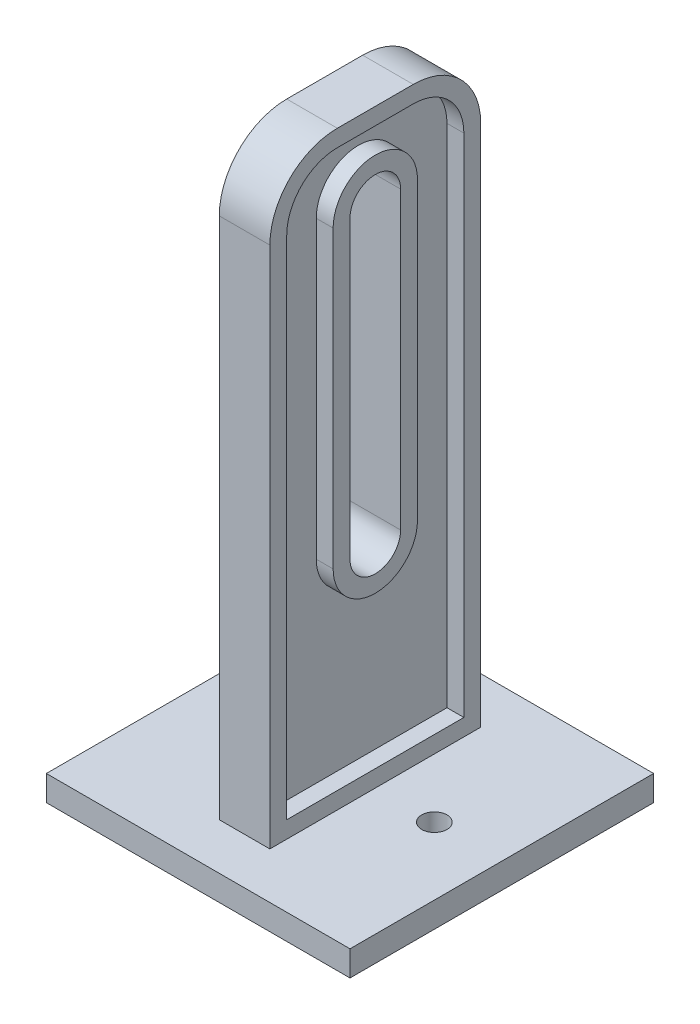
SolidWorks part; units mm, degrees
ref_plane "Front Plane" through (0, 0, 0) normal (0, 0, 1) x (1, 0, 0)
ref_plane "Top Plane" through (0, 0, 0) normal (0, 1, 0) x (1, 0, 0)
ref_plane "Right Plane" through (0, 0, 0) normal (1, 0, 0) x (0, 0, -1)
sketch "Sketch1" plane through (0, 0, 0) normal (0, 1, 0) x (1, 0, 0)
  line L1 (-18, -18) -> (18, -18)
  line L2 (-18, -18) -> (-18, 18)
  line L3 (-18, 18) -> (18, 18)
  line L4 (18, -18) -> (18, 18)
  line L5 (-18, -18) -> (18, 18) construction
  line L6 (-18, 18) -> (18, -18) construction
  point P0 (0, 0)
  dimension "D1" = 36
  dimension "D2" = 36
extrude "Boss-Extrude1" add sketch "Sketch1" along normal blind 3
sketch "Sketch2" plane through (0, 3, 0) normal (0, 1, 0) x (1, 0, 0)
  line L0 (-18, 0) -> (18, 0) construction
  line L1 (-18, 18) -> (-18, -18) construction
  line L2 (18, -18) -> (18, 18) construction
  line L3 (0, -18) -> (0, 18) construction
  line L4 (-18, -18) -> (18, -18) construction
  line L5 (18, 18) -> (-18, 18) construction
  circle A0 centre (10, 0) radius 1.5
  circle A1 centre (-10, 0) radius 1.5
  dimension "D1" = 3
  dimension "D2" = 3
  dimension "D3" = 10
  dimension "D4" = 10
extrude "Cut-Extrude1" cut sketch "Sketch2" against normal blind 3
sketch "Sketch3" plane through (0, 3, 0) normal (0, 1, 0) x (1, 0, 0)
  line L1 (3, -12.5) -> (-3, -12.5)
  line L2 (3, -12.5) -> (3, 12.5)
  line L3 (3, 12.5) -> (-3, 12.5)
  line L4 (-3, -12.5) -> (-3, 12.5)
  line L5 (3, -12.5) -> (-3, 12.5) construction
  line L6 (3, 12.5) -> (-3, -12.5) construction
  point P0 (0, 0)
  dimension "D1" = 6
  dimension "D2" = 25
extrude "Boss-Extrude2" add sketch "Sketch3" along normal blind 70
sketch "Sketch4" plane through (3, 0, 0) normal (1, 0, 0) x (0, 0, -1)
  line L2 (0, 73) -> (0, 0) construction
  line L3 (-12.5, 73) -> (12.5, 73) construction
  line L4 (0, 28) -> (0, 63) construction
  line L5 (-3, 28) -> (-3, 63)
  line L6 (3, 28) -> (3, 63)
  arc A2 (-3, 28) -> (3, 28) centre (0, 28) ccw
  arc A3 (3, 63) -> (-3, 63) centre (0, 63) ccw
  point P11 (0, 45.5)
  dimension "D1" = 3
  dimension "D2" = 35
  dimension "D3" = 10
extrude "Cut-Extrude2" cut sketch "Sketch4" against normal blind 70
fillet "Fillet1" radius 8 1 edges at (0, 73, -12.5)
fillet "Fillet2" radius 8 1 edges at (0, 73, 12.5)
sketch "Sketch5" plane through (3, 0, 0) normal (1, 0, 0) x (0, 0, -1)
  line L34 (4.5, 71) -> (-4.5, 71)
  line L35 (-10.5, 65) -> (-10.5, 5)
  line L36 (-10.5, 5) -> (10.5, 5)
  line L37 (10.5, 5) -> (10.5, 65)
  line L38 (4.5, 71) -> (-4.5, 71)
  line L39 (-10.5, 65) -> (-10.5, 5)
  line L40 (-10.5, 5) -> (10.5, 5)
  line L41 (10.5, 5) -> (10.5, 65)
  line L46 (5, 28) -> (5, 63)
  line L47 (-5, 63) -> (-5, 28)
  line L48 (5, 28) -> (5, 63)
  line L49 (-5, 63) -> (-5, 28)
  arc A18 (-4.5, 71) -> (-10.5, 65) centre (-4.5, 65) ccw
  arc A19 (10.5, 65) -> (4.5, 71) centre (4.5, 65) ccw
  arc A20 (-4.5, 71) -> (-10.5, 65) centre (-4.5, 65) ccw
  arc A21 (10.5, 65) -> (4.5, 71) centre (4.5, 65) ccw
  arc A26 (5, 63) -> (-5, 63) centre (0, 63) ccw
  arc A27 (-5, 28) -> (5, 28) centre (0, 28) ccw
  arc A28 (5, 63) -> (-5, 63) centre (0, 63) ccw
  arc A29 (-5, 28) -> (5, 28) centre (0, 28) ccw
  point P0 (-10.5825, 3)
  dimension "D1" = 2
  dimension "D2" = 2
extrude "Cut-Extrude3" cut sketch "Sketch5" against normal blind 2
